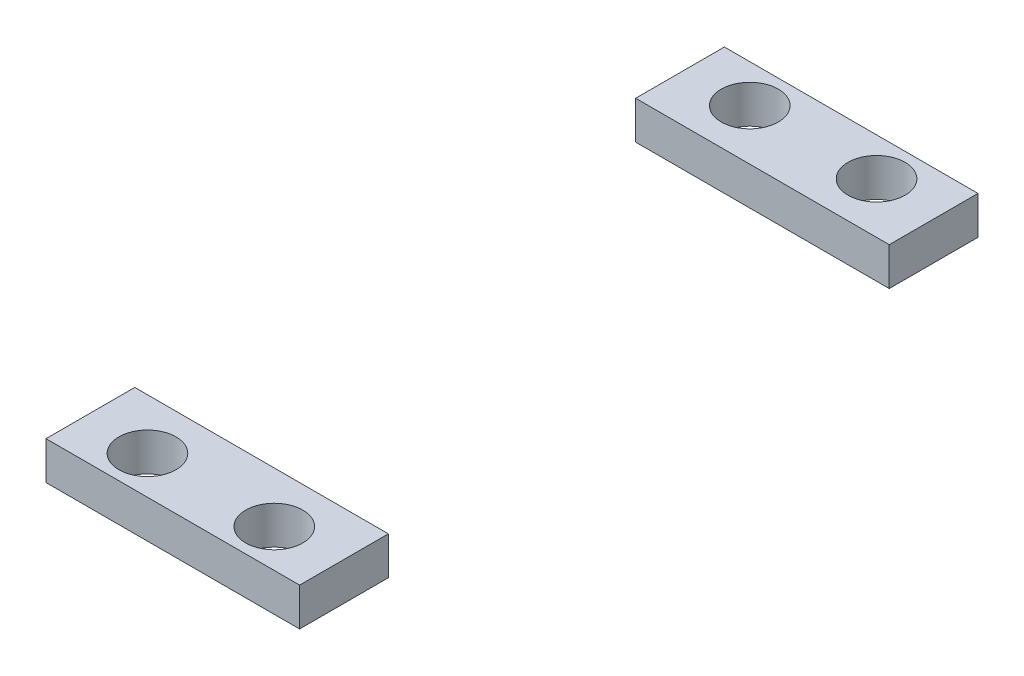
SolidWorks part; units mm, degrees
ref_plane "Front Plane" through (0, 0, 0) normal (0, 0, 1) x (1, 0, 0)
ref_plane "Top Plane" through (0, 0, 0) normal (0, 1, 0) x (1, 0, 0)
ref_plane "Right Plane" through (0, 0, 0) normal (1, 0, 0) x (0, 0, -1)
sketch "Sketch1" plane through (0, 0, 0) normal (0, 1, 0) x (1, 0, 0)
  line L0 (0, 46.5) -> (20, 46.5)
  line L1 (0, 0) -> (20, 0)
  line L2 (0, 0) -> (0, 53.5)
  line L3 (0, 53.5) -> (20, 53.5)
  line L4 (20, 0) -> (20, 53.5)
  line L9 (0, 7) -> (20, 7)
  circle A0 centre (15, 50.5) radius 2.25
  circle A1 centre (5, 50.5) radius 2.25
  circle A2 centre (5, 3) radius 2.25
  circle A3 centre (15, 3) radius 2.25
  dimension "D3" = 3
  dimension "D7" = 3
  dimension "D1" = 20
  dimension "D2" = 53.5
  dimension "D4" = 3
  dimension "D5" = 5
  dimension "D6" = 5
  dimension "D8" = 3
  dimension "D13" = 7
  dimension "D14" = 7
extrude "Boss-Extrude2" add sketch "Sketch1" along normal blind 3
sketch "Sketch3" plane through (20, 0, 0) normal (1, 0, 0) x (0, 0, -1)
  line L0 (71.75, 50) -> (71.75, 4)
  line L1 (7, 0) -> (53.5, 0)
  line L2 (-22.25, 0) -> (-22.25, 54)
  line L3 (0, 0) -> (-22.25, 0)
  line L4 (53.5, 0) -> (75.75, 0)
  line L5 (-22.25, 54) -> (75.75, 54)
  line L6 (75.75, 54) -> (75.75, 0)
  line L7 (-17.1405, 50) -> (-17.1405, 4)
  line L8 (-17.1405, 50) -> (71.75, 50)
  line L9 (71.75, 4) -> (-17.1405, 4)
  dimension "D1" = 4
  dimension "D2" = 4
  dimension "D3" = 98
  dimension "D4" = 54
